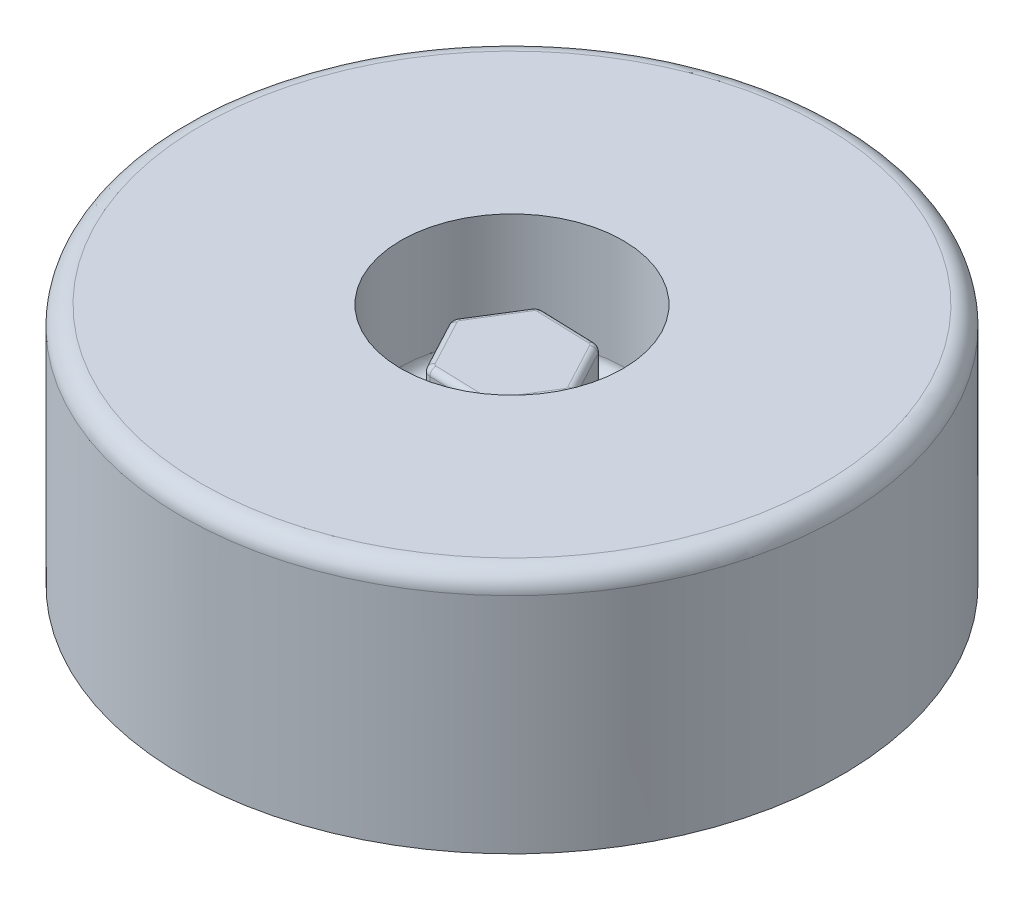
SolidWorks part; units mm, degrees
ref_plane "Front Plane" through (0, 0, 0) normal (0, 0, 1) x (1, 0, 0)
ref_plane "Top Plane" through (0, 0, 0) normal (0, 1, 0) x (1, 0, 0)
ref_plane "Right Plane" through (0, 0, 0) normal (1, 0, 0) x (0, 0, -1)
sketch "Sketch1" plane through (0, 0, 0) normal (0, 1, 0) x (1, 0, 0)
  circle A0 centre (0, 0) radius 2.3241
  circle A1 centre (0, 0) radius 6.8961
  dimension "D1" = 4.572
extrude "Boss-Extrude1" add sketch "Sketch1" along normal blind 2.794
sketch "Sketch2" plane through (0, 0, 0) normal (0, -1, 0) x (1, 0, 0)
  circle A0 centre (0, 0) radius 2.3241 construction
  circle A1 centre (0, 0) radius 2.3241
extrude "Boss-Extrude2" add sketch "Sketch2" against normal blind 0.254
sketch "Sketch3" plane through (0, 0.254, 0) normal (0, 1, 0) x (1, 0, 0)
  line L6 (-0.6403, 1.225) -> (0.7631, 1.179) construction
  line L7 (-1.3818, 0.0326) -> (-0.6403, 1.225) construction
  line L8 (-0.72, -1.2058) -> (-1.3818, 0.0326) construction
  line L9 (0.6834, -1.2518) -> (-0.72, -1.2058) construction
  line L10 (1.425, -0.0594) -> (0.6834, -1.2518) construction
  line L11 (0.7631, 1.179) -> (1.425, -0.0594) construction
  line L12 (-0.4958, 1.1567) -> (0.6144, 1.1203)
  line L13 (0.7762, 1.0197) -> (1.2998, 0.04)
  line L14 (1.2936, -0.1504) -> (0.707, -1.0937)
  line L15 (0.5389, -1.1835) -> (-0.5713, -1.1471)
  line L16 (-0.7331, -1.0465) -> (-1.2567, -0.0668)
  line L17 (-1.2505, 0.1236) -> (-0.6638, 1.0669)
  line L18 (-0.6057, 1.1603) -> (0.7244, 1.1167) construction
  line L19 (0.7244, 1.1167) -> (1.3517, -0.057) construction
  line L20 (-1.3085, 0.0302) -> (-0.6057, 1.1603) construction
  line L21 (-0.6812, -1.1435) -> (-1.3085, 0.0302) construction
  line L22 (0.6489, -1.1871) -> (-0.6812, -1.1435) construction
  line L23 (1.3517, -0.057) -> (0.6489, -1.1871) construction
  arc A0 (0.6144, 1.1203) -> (0.7762, 1.0197) centre (0.6082, 0.9299) cw
  arc A1 (-0.4958, 1.1567) -> (-0.6638, 1.0669) centre (-0.502, 0.9663) ccw
  arc A2 (-1.2567, -0.0668) -> (-1.2505, 0.1236) centre (-1.0887, 0.023) cw
  arc A3 (-0.5713, -1.1471) -> (-0.7331, -1.0465) centre (-0.5651, -0.9567) cw
  arc A4 (0.707, -1.0937) -> (0.5389, -1.1835) centre (0.5452, -0.9931) cw
  arc A5 (1.2998, 0.04) -> (1.2936, -0.1504) centre (1.1318, -0.0498) cw
  dimension "D2" = 0.1905
  dimension "D1" = 0.0635
extrude "Boss-Extrude3" add sketch "Sketch3" along normal blind 1.651
sketch "Sketch4" plane through (0, 0, 0) normal (0, -1, 0) x (1, 0, 0)
  circle A1 centre (0, 0) radius 6.8961
  circle A2 centre (0, 0) radius 6.8961
  dimension "D1" = 0
extrude "Boss-Extrude4" add sketch "Sketch4" along normal blind 2.286
fillet "Fillet1" radius 0.254 13 edges at (0.0593, 0.254, -1.1385) (-0.5918, 0.254, -1.1343) (-0.9571, 0.254, -0.5952) (-1.2791, 0.254, -0.0292) (-0.9949, 0.254, 0.5567) (-0.6657, 0.254, 1.1185) (-0.0162, 0.254, 1.1653) (0.635, 0.254, 1.1611) (1.0003, 0.254, 0.6221) (1.3222, 0.254, 0.056) (1.038, 0.254, -0.5298) (0.7088, 0.254, -1.0917) (0, 0.254, -2.3241)
fillet "Fillet2" radius 0.127 12 edges at (-0.6657, 1.905, 1.1185) (-0.9949, 1.905, 0.5567) (-1.2791, 1.905, -0.0292) (-0.9571, 1.905, -0.5952) (-0.5918, 1.905, -1.1343) (0.0593, 1.905, -1.1385) (0.7088, 1.905, -1.0917) (1.038, 1.905, -0.5298) (1.3222, 1.905, 0.056) (1.0003, 1.905, 0.6221) (0.635, 1.905, 1.1611) (-0.0162, 1.905, 1.1653)
fillet "Fillet3" radius 0.4 1 edges at (0, 2.794, 6.8961)
